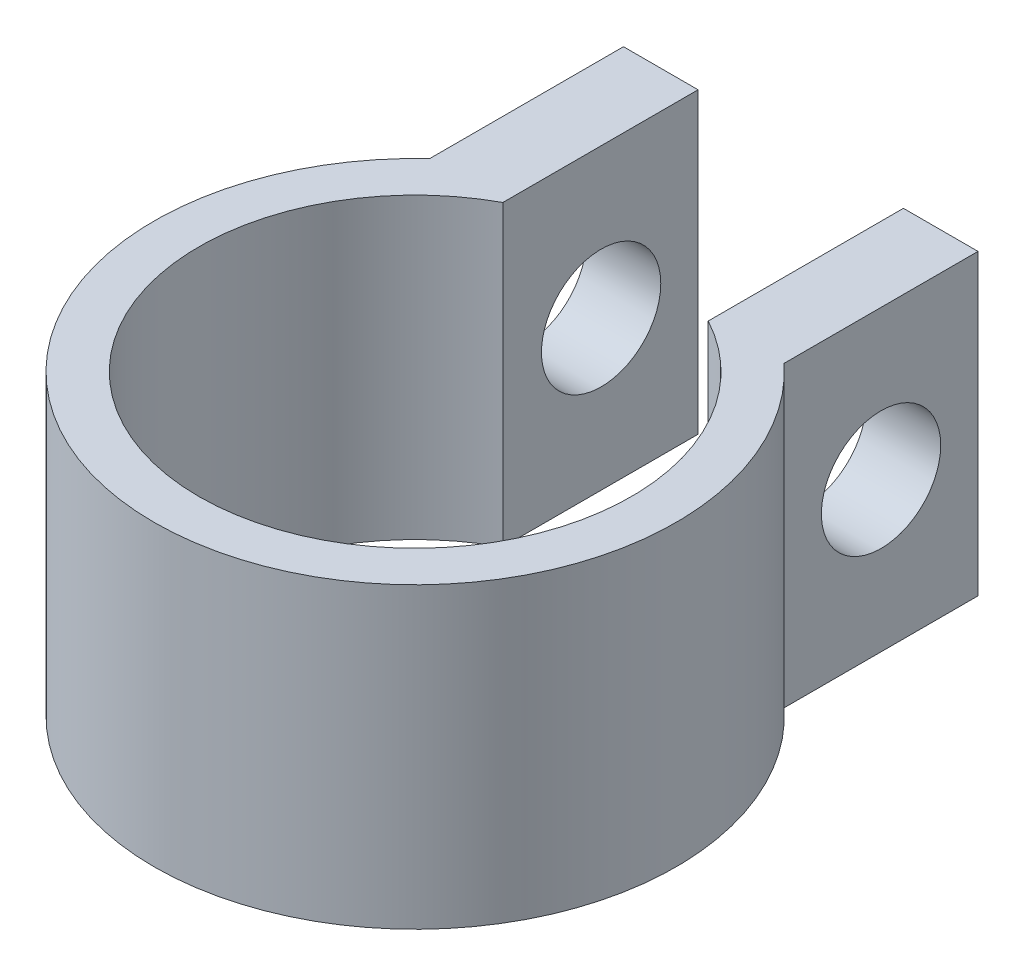
SolidWorks part; units mm, degrees
ref_plane "Front Plane" through (0, 0, 0) normal (0, 0, 1) x (1, 0, 0)
ref_plane "Top Plane" through (0, 0, 0) normal (0, 1, 0) x (1, 0, 0)
ref_plane "Right Plane" through (0, 0, 0) normal (1, 0, 0) x (0, 0, -1)
sketch "Sketch1" plane through (0, 0, 0) normal (0, 1, 0) x (1, 0, 0)
  line L0 (-5.9412, 6.4238) -> (-5.9412, 12.9238)
  line L1 (-5.9412, 12.9238) -> (-3.4412, 12.9238)
  line L2 (-3.4412, 12.9238) -> (-3.4412, 8.0449)
  line L3 (5.9412, 6.4238) -> (5.9412, 12.9238)
  line L4 (5.9412, 12.9238) -> (3.4412, 12.9238)
  line L5 (3.4412, 12.9238) -> (3.4412, 8.0449)
  line L6 (-3.4412, 8.0449) -> (-3.4412, 6.3813)
  line L7 (3.4412, 8.0449) -> (3.4412, 6.3813)
  arc A0 (-5.9412, 6.4238) -> (5.9412, 6.4238) centre (0, 0) ccw
  arc A1 (3.4412, 8.0449) -> (-3.4412, 8.0449) centre (0, 0) ccw
  circle A2 centre (0, 0) radius 7.25
  dimension "D1" = 17.5
  dimension "D2" = 1.5
  dimension "D3" = 2.5
  dimension "D4" = 6.5
extrude "Boss-Extrude1" add sketch "Sketch1" along normal blind 10 contours A2 L6 L2 L1 L0 A0 L3 L4 L5 L7
sketch "Sketch2" plane through (5.9412, 0, 0) normal (1, 0, 0) x (0, 0, -1)
  line L0 (6.4238, 10) -> (12.9238, 10) construction
  line L1 (12.9238, 10) -> (12.9238, 0) construction
  circle A0 centre (9.6738, 5) radius 2
  point P2 (9.6738, 5.1702)
  point P5 (9.6738, 10)
  point P8 (12.9238, 5)
  dimension "D1" = 4
extrude "Cut-Extrude1" cut sketch "Sketch2" against normal through all
